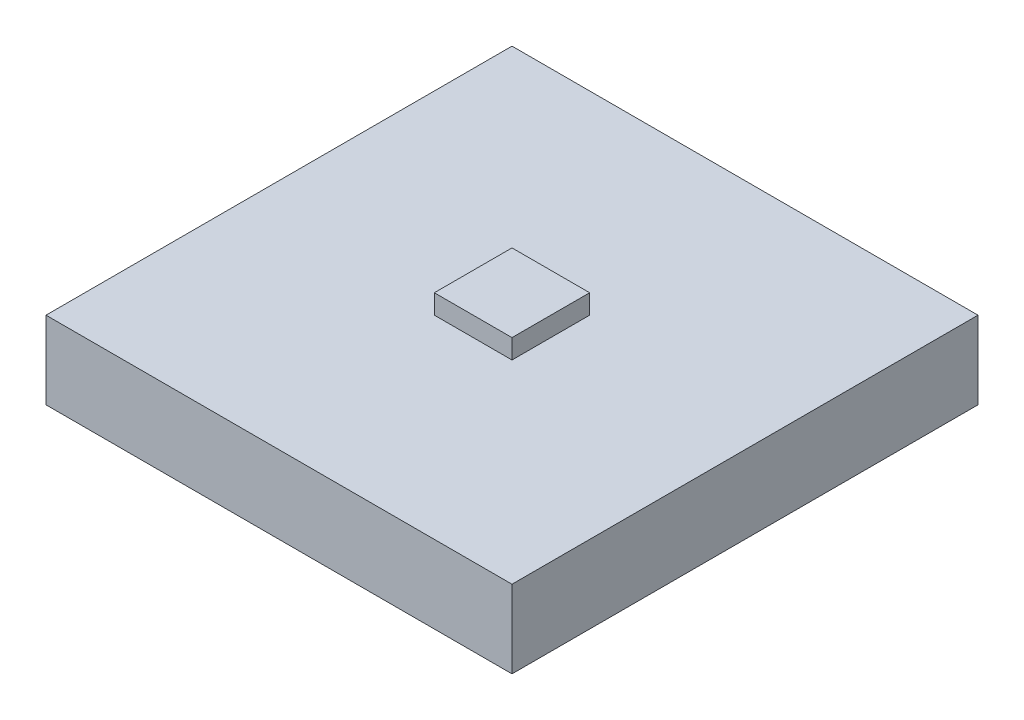
SolidWorks part; units mm, degrees
ref_plane "Front Plane" through (0, 0, 0) normal (0, 0, 1) x (1, 0, 0)
ref_plane "Top Plane" through (0, 0, 0) normal (0, 1, 0) x (1, 0, 0)
ref_plane "Right Plane" through (0, 0, 0) normal (1, 0, 0) x (0, 0, -1)
sketch "Sketch1" plane through (0, 0, 0) normal (0, 1, 0) x (1, 0, 0)
  line L1 (0, 0) -> (76.2, 0)
  line L2 (0, 0) -> (0, 76.2)
  line L3 (0, 76.2) -> (76.2, 76.2)
  line L4 (76.2, 0) -> (76.2, 76.2)
  dimension "D1" = 76.2
  dimension "D2" = 76.2
extrude "Boss-Extrude1" add sketch "Sketch1" along normal blind 12.7
sketch "Sketch2" plane through (0, 12.7, 0) normal (0, 1, 0) x (1, 0, 0)
  line L0 (0, 76.2) -> (0, 0) construction
  line L1 (31.75, 31.75) -> (44.45, 31.75)
  line L2 (31.75, 31.75) -> (31.75, 44.45)
  line L3 (31.75, 44.45) -> (44.45, 44.45)
  line L4 (44.45, 31.75) -> (44.45, 44.45)
  line L5 (0, 0) -> (76.2, 0) construction
  dimension "D1" = 12.7
  dimension "D2" = 12.7
  dimension "D3" = 31.75
  dimension "D4" = 31.75
extrude "Boss-Extrude2" add sketch "Sketch2" along normal blind 3.175 contours L3 L4 L1 L2
